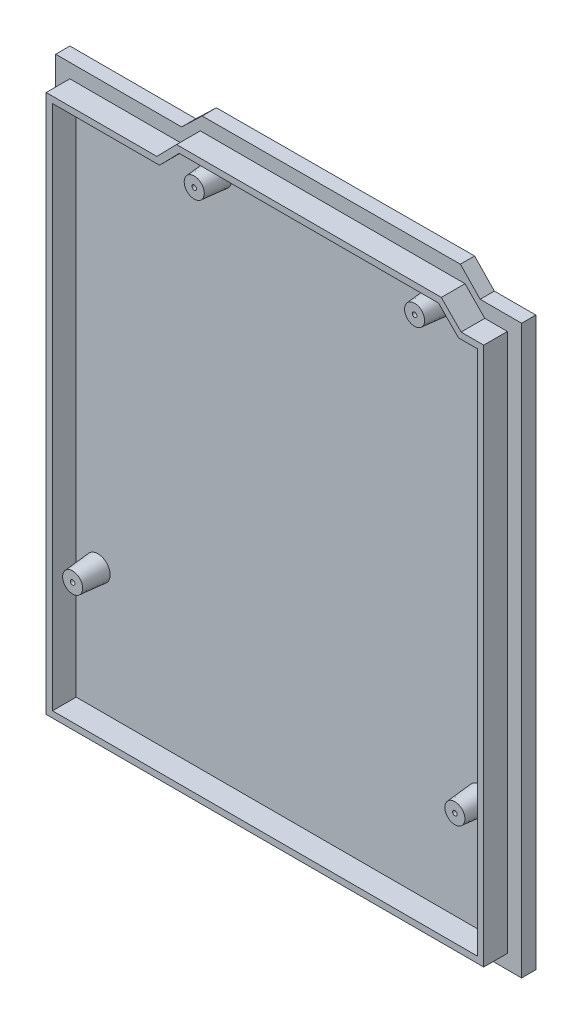
SolidWorks part; units mm, degrees
ref_plane "Front Plane" through (0, 0, 0) normal (1, 0, 0) x (0, 1, 0)
ref_plane "Top Plane" through (0, 0, 0) normal (0, 0, 1) x (0, 1, 0)
ref_plane "Right Plane" through (0, 0, 0) normal (0, 1, 0) x (-1, 0, 0)
sketch "Sketch1" plane through (0, 0, 0) normal (0, 0, 1) x (0, 1, 0)
  line L9 (40.6099, 53.4526) -> (-31.1901, 53.4526)
  line L10 (-31.1901, 53.4526) -> (-31.1901, -5.5474)
  line L11 (-31.1901, -5.5474) -> (40.6099, -5.5474)
  line L13 (43.1099, 34.9026) -> (43.2099, 2.2026)
  line L17 (40.6099, -5.5474) -> (40.6099, -0.2974)
  line L18 (40.6099, -0.2974) -> (43.2099, 2.2026)
  line L21 (43.1099, 34.9026) -> (40.6099, 37.5026)
  line L22 (40.6099, 37.5026) -> (40.6099, 53.4526)
extrude "Boss-Extrude1" add sketch "Sketch1" along normal blind 1.8
sketch "Sketch5" plane through (0, 0, 0) normal (0, 0, 1) x (0, 1, 0)
  line L0 (-28.5901, 50.8526) -> (-28.5901, -2.9474)
  line L1 (-28.5901, -2.9474) -> (38.0099, -2.9474)
  line L2 (38.0099, -2.9474) -> (38.0099, -0.5474)
  line L3 (38.0099, -0.5474) -> (40.5604, 1.9529)
  line L4 (40.5604, 1.9529) -> (40.5604, 34.8056)
  line L5 (40.5604, 34.8056) -> (38.0099, 37.3059)
  line L6 (38.0099, 37.3059) -> (38.0099, 50.8526)
  line L8 (38.0099, 50.8526) -> (-28.5901, 50.8526)
  line L19 (40.6099, 53.4526) -> (-31.1901, 53.4526) construction
  line L24 (-31.1901, 53.4526) -> (-31.1901, -5.5474) construction
  line L31 (40.6099, 37.5026) -> (40.6099, 53.4526) construction
  line L33 (40.6099, -5.5474) -> (40.6099, -0.2974) construction
  line L34 (43.2099, 2.2026) -> (43.1099, 34.9026) construction
  line L35 (-31.1901, -5.5474) -> (40.6099, -5.5474) construction
  point P2 (0, 0)
  point P19 (40.5604, 18.3793)
  point P22 (0, 0)
  dimension "D1" = 2.6
  dimension "D2" = 2.6
  dimension "D3" = 2.6
  dimension "D4" = 2.6
  dimension "D5" = 2.6
  dimension "D6" = 2.6
extrude "Extrude-Thin1" add sketch "Sketch5" along normal blind 3 from surface at 1.8 thin
sketch "Sketch7" plane through (0, 0, 1.8) normal (0, 0, 1) x (1, 0, 0)
  line L1 (2.9474, 38.0099) -> (0.5474, 38.0099) construction
  line L2 (-34.8056, 40.5604) -> (-1.9529, 40.5604) construction
  line L3 (2.9474, 38.0099) -> (2.9474, -28.5901) construction
  line L4 (-50.8526, 38.0099) -> (-50.8526, -28.5901) construction
  line L5 (-50.8526, 38.0099) -> (-37.3059, 38.0099) construction
  circle A0 centre (-4.8026, 37.9604) radius 1.55
  circle A1 centre (-32.7026, 37.9604) radius 1.55
  circle A2 centre (0.2974, -14.1401) radius 1.55
  circle A3 centre (-48.1026, -13.0401) radius 1.55
  point P2 (0, 0)
  point P9 (0, 0)
  point P10 (0, 0)
  dimension "D1" = 3.1
  dimension "D6" = 2.75
  dimension "D2" = 2.6
  dimension "D3" = 7.75
  dimension "D4" = 0
  dimension "D5" = 27.9
  dimension "D7" = 2.65
  dimension "D8" = 52.15
  dimension "D9" = 51.05
extrude "Extrude-Thin2" add sketch "Sketch7" along normal blind 3.2 draft 5 thin thin type one direction reverse wall 1.54
